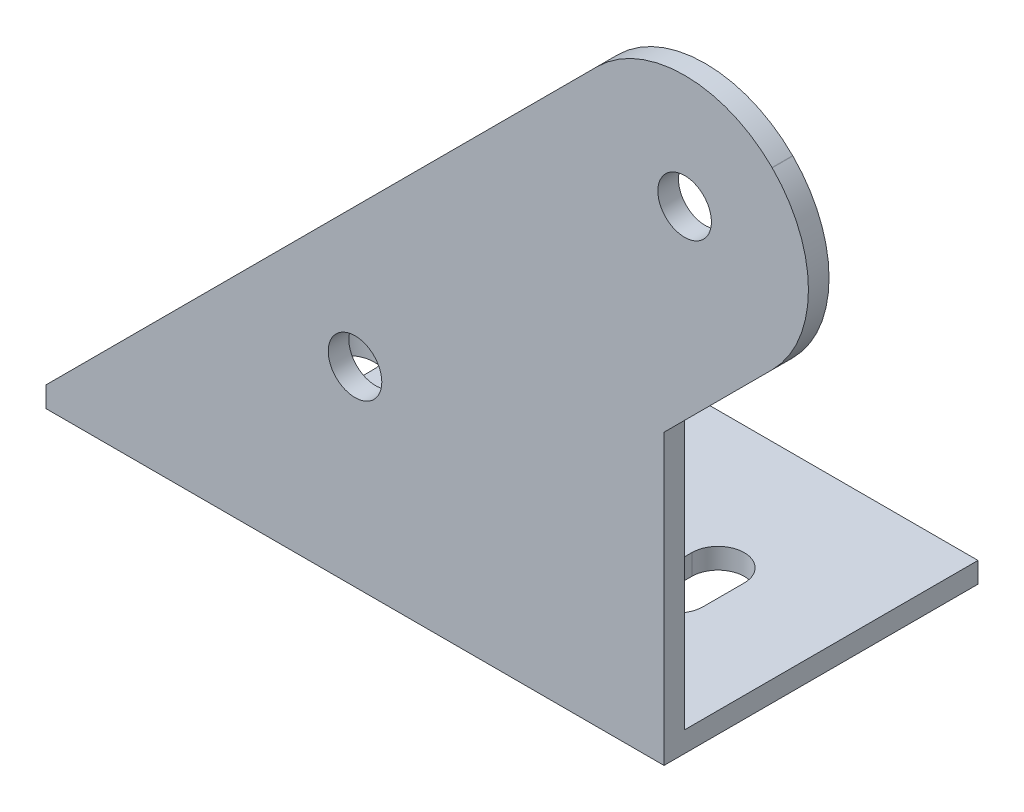
SolidWorks part; units mm, degrees
material "Fundición maleable"
ref_plane "Alzado" through (0, 0, 0) normal (0, 0, 1) x (1, 0, 0)
ref_plane "Planta" through (0, 0, 0) normal (0, 1, 0) x (1, 0, 0)
ref_plane "Vista lateral" through (0, 0, 0) normal (1, 0, 0) x (0, 0, -1)
sketch "Croquis1" plane through (0, 0, 0) normal (0, 0, 1) x (1, 0, 0)
  line L0 (75, 0) -> (-75, 0)
  line L1 (-75, 0) -> (-21.2132, 53.7868)
  line L2 (21.2132, 53.7868) -> (75, 0)
  arc A0 (-21.2132, 53.7868) -> (21.2132, 53.7868) centre (0, 32.5736) cw
  circle A1 centre (0, 41.3259) radius 6.5
  point P4 (0, 0)
  dimension "D2" = 30
  dimension "D3" = 13
  dimension "D1" = 150
extrude "Saliente-Extruir1" add sketch "Croquis1" along normal blind 5
sketch "Croquis2" plane through (0, 0, 0) normal (0, -1, 0) x (1, 0, 0)
  line L0 (75, 5) -> (75, 0) construction
  line L1 (-75, -71.2) -> (75, -71.2)
  line L2 (-75, -71.2) -> (-75, 5)
  line L3 (-75, 5) -> (75, 5)
  line L4 (75, -71.2) -> (75, 5)
  line L5 (-75, -33.1) -> (75, -33.1) construction
  line L6 (-45, -28.1) -> (-45, -38.1) construction
  line L7 (-38.4816, -28.1) -> (-38.4816, -38.1)
  line L8 (-51.5184, -28.1) -> (-51.5184, -38.1)
  line L9 (45, -28.1) -> (45, -38.1) construction
  line L10 (51.3725, -28.1) -> (51.3725, -38.1)
  line L11 (38.6275, -28.1) -> (38.6275, -38.1)
  arc A2 (-38.4816, -28.1) -> (-51.5184, -28.1) centre (-45, -28.1) ccw
  arc A3 (-51.5184, -38.1) -> (-38.4816, -38.1) centre (-45, -38.1) ccw
  arc A4 (51.3725, -28.1) -> (38.6275, -28.1) centre (45, -28.1) ccw
  arc A5 (38.6275, -38.1) -> (51.3725, -38.1) centre (45, -38.1) ccw
  point P14 (-45, -33.1)
  point P20 (45, -33.1)
  dimension "D2" = 5
  dimension "D3" = 5
  dimension "D1" = 76.2
extrude "Saliente-Extruir2" add sketch "Croquis2" along normal blind 5
sketch "Croquis3" plane through (0, 0, 0) normal (0, 0, -1) x (-1, 0, 0)
  line L0 (-75, -5) -> (75, -5) construction
  line L1 (75, 0) -> (-58.7868, 133.7868)
  line L2 (-101.2132, 133.7868) -> (-101.2632, 133.7368)
  line L3 (-101.2632, 91.3104) -> (-75, 65.0473)
  line L6 (-75, 0) -> (75, 0)
  line L7 (-75, 0) -> (-75, 65.0473)
  circle A0 centre (-80, 115) radius 6.5
  arc A1 (-101.2632, 133.7368) -> (-101.2632, 91.3104) centre (-80.05, 112.5236) ccw
  arc A2 (-58.7868, 133.7868) -> (-101.2132, 133.7868) centre (-80, 112.5736) ccw
  circle A3 centre (0, 41.3259) radius 10
  dimension "D1" = 13
  dimension "D4" = 30
  dimension "D2" = 120
  dimension "D3" = 80
extrude "Saliente-Extruir3" add sketch "Croquis3" against normal up to surface (5 mm away) up to face at (0, 17.7267, 5)
